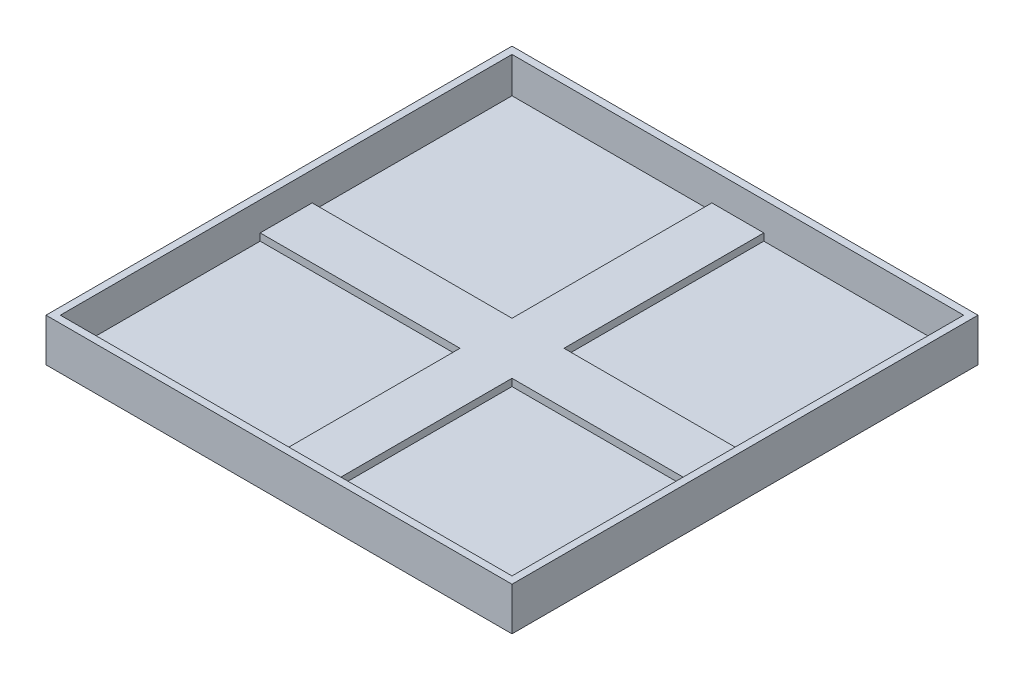
SolidWorks part; units mm, degrees
ref_plane "Front Plane" through (0, 0, 0) normal (0, 0, 1) x (1, 0, 0)
ref_plane "Top Plane" through (0, 0, 0) normal (0, 1, 0) x (1, 0, 0)
ref_plane "Right Plane" through (0, 0, 0) normal (1, 0, 0) x (0, 0, -1)
sketch "Sketch1" plane through (0, 0, 0) normal (0, 1, 0) x (1, 0, 0)
  line L1 (126, 126) -> (-126, 126)
  line L2 (126, 126) -> (126, -126)
  line L3 (126, -126) -> (-126, -126)
  line L4 (-126, 126) -> (-126, -126)
  line L5 (126, 126) -> (-126, -126) construction
  line L6 (126, -126) -> (-126, 126) construction
  point P0 (0, 0)
  point P6 (0, 0)
  point P11 (0, 0)
  dimension "D1" = 252
  dimension "D2" = 252
extrude "Boss-Extrude1" add sketch "Sketch1" along normal blind 4
sketch "Sketch2" plane through (0, 4, 0) normal (0, 1, 0) x (1, 0, 0)
  line L1 (126, 14.5) -> (-126, 14.5)
  line L2 (126, 14.5) -> (126, -14.5)
  line L3 (126, -14.5) -> (-126, -14.5)
  line L4 (-126, 14.5) -> (-126, -14.5)
  line L5 (126, 14.5) -> (-126, -14.5) construction
  line L6 (126, -14.5) -> (-126, 14.5) construction
  line L7 (14.5, 126) -> (-14.5, 126)
  line L8 (14.5, 126) -> (14.5, -126)
  line L9 (14.5, -126) -> (-14.5, -126)
  line L10 (-14.5, 126) -> (-14.5, -126)
  line L11 (14.5, 126) -> (-14.5, -126) construction
  line L12 (14.5, -126) -> (-14.5, 126) construction
  point P0 (0, 0)
  point P7 (0, 0)
  dimension "D1" = 29
  dimension "D2" = 29
  dimension "D3" = 252
  dimension "D4" = 252
extrude "Boss-Extrude2" add sketch "Sketch2" along normal blind 4
sketch "Sketch3" plane through (0, 0, 0) normal (0, -1, 0) x (1, 0, 0)
  line L0 (-130, 130) -> (-130, -130)
  line L1 (126, 126) -> (-126, 126)
  line L2 (126, 126) -> (126, -126)
  line L3 (126, -126) -> (-126, -126)
  line L4 (-126, 126) -> (-126, -126)
  line L5 (126, 126) -> (-126, -126) construction
  line L6 (126, -126) -> (-126, 126) construction
  line L7 (130, -130) -> (-130, -130)
  line L8 (130, 130) -> (130, -130)
  line L9 (130, 130) -> (-130, 130)
  point P0 (0, 0)
  dimension "D1" = 4
extrude "Boss-Extrude3" add sketch "Sketch3" against normal blind 24
